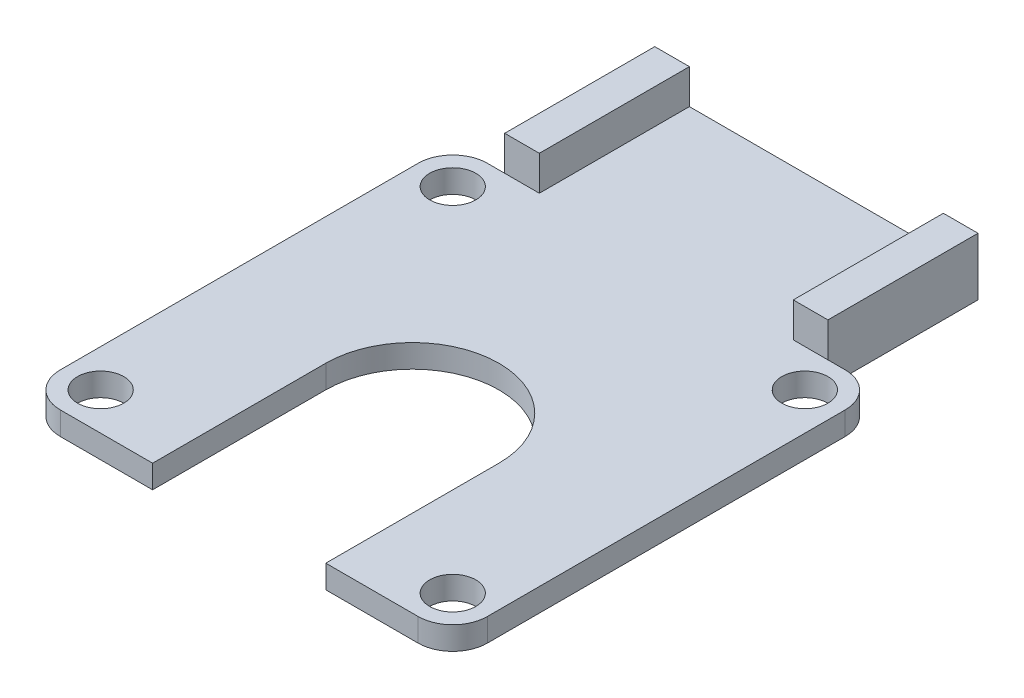
SolidWorks part; units mm, degrees
material "ABS PC"
ref_plane "Front Plane" through (0, 0, 0) normal (0, 0, 1) x (1, 0, 0)
ref_plane "Top Plane" through (0, 0, 0) normal (0, 1, 0) x (1, 0, 0)
ref_plane "Right Plane" through (0, 0, 0) normal (1, 0, 0) x (0, 0, -1)
sketch "Sketch1" plane through (0, 0, 0) normal (0, 1, 0) x (1, 0, 0)
  line L1 (18.5, -18.5) -> (-18.5, -18.5)
  line L2 (18.5, -18.5) -> (18.5, 18.5)
  line L3 (18.5, 18.5) -> (-18.5, 18.5)
  line L4 (-18.5, -18.5) -> (-18.5, 18.5)
  line L5 (18.5, -18.5) -> (-18.5, 18.5) construction
  line L6 (18.5, 18.5) -> (-18.5, -18.5) construction
  point P0 (0, 0)
  dimension "D1" = 37
extrude "Boss-Extrude1" add sketch "Sketch1" along normal blind 2
fillet "Fillet1" radius 3 4 edges at (-18.5, 1, -18.5) (18.5, 1, -18.5) (18.5, 1, 18.5) (-18.5, 1, 18.5)
hole_wizard "Ø4.0 (4) Diameter Hole1" positions "Sketch3" profile "Sketch4" hole size "Ø4.0" standard "ANSI Metric" end condition through all
sketch "Sketch3" plane through (0, 2, 0) normal (0, 1, 0) x (1, 0, 0)
  line L1 (15.25, -15.25) -> (-15.25, -15.25)
  line L2 (15.25, -15.25) -> (15.25, 15.25)
  line L3 (15.25, 15.25) -> (-15.25, 15.25)
  line L4 (-15.25, -15.25) -> (-15.25, 15.25)
  line L5 (15.25, -15.25) -> (-15.25, 15.25) construction
  line L6 (15.25, 15.25) -> (-15.25, -15.25) construction
  point P2 (-15.25, 15.25)
  point P5 (15.25, -15.25)
  point P6 (15.25, 15.25)
  point P7 (-15.25, -15.25)
  dimension "D1" = 30.5
sketch "Sketch4" plane through (-15.25, 2, -15.25) normal (1, 0, 0) x (0, 0, 1)
  line L0 (0, 0) -> (0, 2)
  line L1 (0, 2) -> (2, 2)
  line L2 (2, 2) -> (2, 0)
  line L5 (2, 0) -> (0, 0)
  line L11 (0, -6.35) -> (0, 107.95) construction
  dimension "Thru Hole Dia." = 4
  dimension "Thru Hole Depth" = 2
sketch "Sketch6" plane through (0, 2, 0) normal (0, 1, 0) x (1, 0, 0)
  line L0 (15.5, 18.5) -> (-15.5, 18.5) construction
  line L1 (14, 18.5) -> (-14, 18.5)
  line L2 (14, 18.5) -> (14, 31.5)
  line L3 (14, 31.5) -> (-14, 31.5)
  line L4 (-14, 18.5) -> (-14, 31.5)
  line L5 (14, 18.5) -> (-14, 31.5) construction
  line L6 (14, 31.5) -> (-14, 18.5) construction
  line L7 (0, 25) -> (0, 0) construction
  line L8 (-15.5, -18.5) -> (15.5, -18.5) construction
  point P0 (0, 25)
  dimension "D1" = 28
  dimension "D2" = 50
extrude "Boss-Extrude3" add sketch "Sketch6" against normal through all
sketch "Sketch7" plane through (0, 2, 0) normal (0, 1, 0) x (1, 0, 0)
  line L0 (14, 31.5) -> (-14, 31.5) construction
  line L1 (-14, 31.5) -> (-11, 31.5)
  line L2 (-14, 31.5) -> (-14, 18.5)
  line L3 (-14, 18.5) -> (-11, 18.5)
  line L4 (-11, 31.5) -> (-11, 18.5)
  line L5 (-14, 31.5) -> (-14, 18.5) construction
  line L6 (0, 36.3056) -> (0, -22.6501) construction
  line L7 (11, 31.5) -> (11, 18.5)
  line L8 (14, 18.5) -> (11, 18.5)
  line L9 (14, 31.5) -> (14, 18.5)
  line L10 (14, 31.5) -> (11, 31.5)
  dimension "D1" = 3
extrude "Boss-Extrude4" add sketch "Sketch7" along normal blind 3
sketch "Sketch8" plane through (0, 2, 0) normal (0, 1, 0) x (1, 0, 0)
  line L0 (-15.5, -18.5) -> (15.5, -18.5) construction
  line L1 (7.5, -3.5) -> (-7.5, -3.5)
  line L2 (7.5, -3.5) -> (7.5, -18.5)
  line L3 (7.5, -18.5) -> (-7.5, -18.5)
  line L4 (-7.5, -3.5) -> (-7.5, -18.5)
  line L5 (7.5, -3.5) -> (-7.5, -18.5) construction
  line L6 (7.5, -18.5) -> (-7.5, -3.5) construction
  line L7 (0, 0) -> (0, -11) construction
  arc A0 (7.5, -3.5) -> (-7.5, -3.5) centre (0, -3.5) ccw
  point P0 (0, -11)
  line M18 (-15.5, -18.5) -> (15.5, -18.5)
  dimension "D1" = 15
  dimension "D2" = 15
extrude "Cut-Extrude1" cut sketch "Sketch8" against normal through all contours L1 A0 | L1 L4 L2 M18
